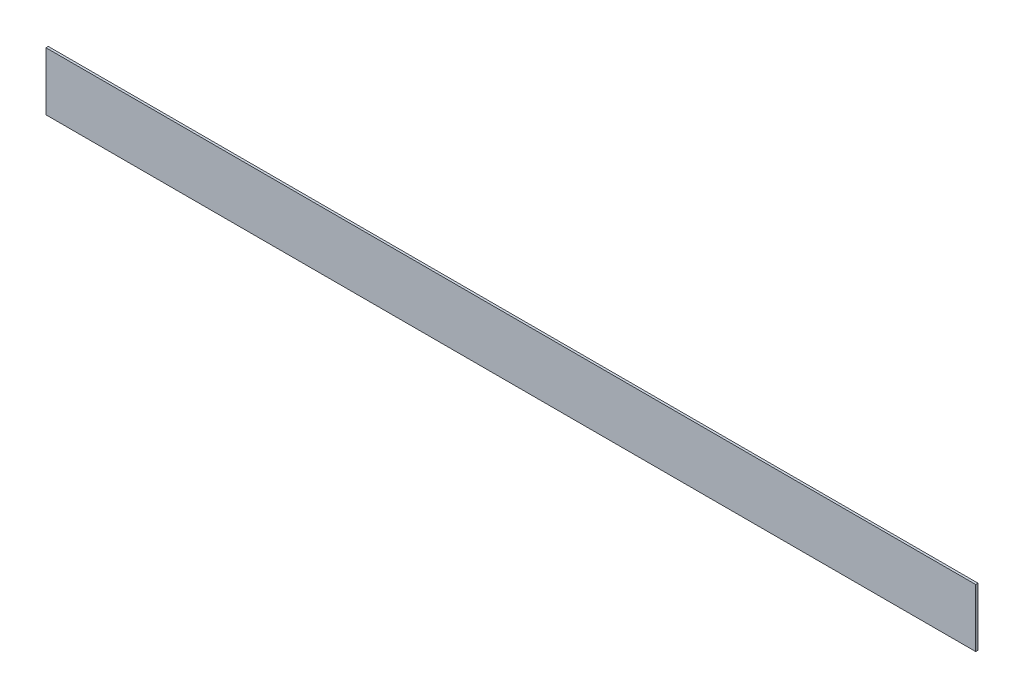
SolidWorks part; units mm, degrees
ref_plane "Front Plane" through (0, 0, 0) normal (0, 0, 1) x (1, 0, 0)
ref_plane "Top Plane" through (0, 0, 0) normal (0, 1, 0) x (1, 0, 0)
ref_plane "Right Plane" through (0, 0, 0) normal (1, 0, 0) x (0, 0, -1)
sketch "Sketch1" plane through (0, 0, 0) normal (0, 0, 1) x (1, 0, 0)
  line L0 (400, -1850) -> (400, 130) construction
  line L1 (-400, -1850) -> (-400, 130) construction
  line L4 (530, -1745) -> (530, -1695)
  line L5 (530, -1695) -> (-530, -1695)
  line L6 (-530, -1695) -> (-530, -1745)
  line L7 (-530, -1745) -> (530, -1745)
  line L8 (400, -1745) -> (400, -1695)
  line L9 (400, -1695) -> (-400, -1695)
  line L10 (-400, -1695) -> (-400, -1745)
  line L11 (-400, -1745) -> (400, -1745)
  dimension "D1" = 0
extrude "Boss-Extrude1" add sketch "Sketch1" along normal blind 2
